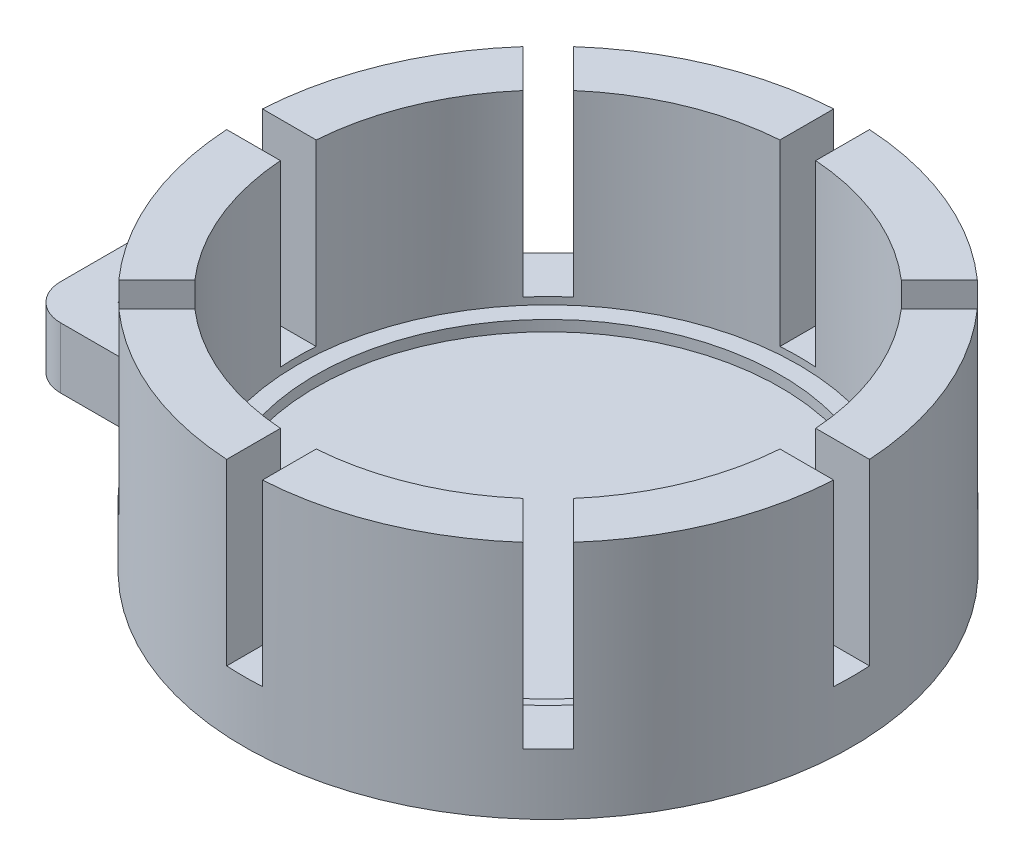
SolidWorks part; units mm, degrees
ref_plane "Спереди" through (0, 0, 0) normal (0, 0, 1) x (1, 0, 0)
ref_plane "Сверху" through (0, 0, 0) normal (0, 1, 0) x (1, 0, 0)
ref_plane "Справа" through (0, 0, 0) normal (1, 0, 0) x (0, 0, -1)
sketch "Эскиз1" plane through (0, 0, 0) normal (0, 1, 0) x (1, 0, 0)
  circle A0 centre (0, 0) radius 8.5
  dimension "D1" = 17
extrude "Бобышка-Вытянуть1" add sketch "Эскиз1" along normal blind 1.2
sketch "Эскиз2" plane through (0, 1.2, 0) normal (0, 1, 0) x (1, 0, 0)
  circle A0 centre (0, 0) radius 7
  circle A1 centre (0, 0) radius 8.5 construction
  circle A2 centre (0, 0) radius 8.5
  dimension "D1" = 14
extrude "Бобышка-Вытянуть2" add sketch "Эскиз2" along normal blind 5.5
sketch "Эскиз3" plane through (0, 1.2, 0) normal (0, 1, 0) x (1, 0, 0)
  circle A0 centre (0, 0) radius 7 construction
  circle A1 centre (0, 0) radius 7
  circle A2 centre (0, 0) radius 6.5
  dimension "D1" = 13
extrude "Бобышка-Вытянуть3" add sketch "Эскиз3" along normal blind 0.3
sketch "Эскиз4" plane through (0, 6.7, 0) normal (0, 1, 0) x (1, 0, 0)
  line L1 (0.5, 5.6513) -> (-0.5, 5.6513)
  line L2 (0.5, 5.6513) -> (0.5, 9.7336)
  line L3 (0.5, 9.7336) -> (-0.5, 9.7336)
  line L4 (-0.5, 5.6513) -> (-0.5, 9.7336)
  line L5 (0.5, 5.6513) -> (-0.5, 9.7336) construction
  line L6 (0.5, 9.7336) -> (-0.5, 5.6513) construction
  point P0 (0, 7.6924)
  point P5 (0, 0)
  dimension "D1" = 1
extrude "Вырез-Вытянуть1" cut sketch "Эскиз4" against normal blind 5
pattern_circular "Круговой массив1" count 8 over 360 about axis through (0, 0, 0) along (0, 1, 0) of "Вырез-Вытянуть1"
sketch "Эскиз5" plane through (0, 0, 0) normal (0, -1, 0) x (1, 0, 0)
  line L1 (-11.124, -2.5) -> (-8.124, -2.5)
  line L2 (-12.124, -1.5) -> (-12.124, 1.5)
  line L3 (-11.124, 2.5) -> (-8.124, 2.5)
  line L5 (-12.124, -2.5) -> (-8.124, 2.5) construction
  line L6 (-12.124, 2.5) -> (-8.124, -2.5) construction
  line L7 (-9.424, 1.2) -> (-10.824, 1.2)
  line L8 (-9.424, 1.2) -> (-9.424, -1.2)
  line L9 (-9.424, -1.2) -> (-10.824, -1.2)
  line L10 (-10.824, 1.2) -> (-10.824, -1.2)
  line L11 (-9.424, 1.2) -> (-10.824, -1.2) construction
  line L12 (-9.424, -1.2) -> (-10.824, 1.2) construction
  circle A0 centre (0, 0) radius 8.5 construction
  arc A1 (-8.124, 2.5) -> (-8.124, -2.5) centre (0, 0) ccw
  arc A2 (-11.124, 2.5) -> (-12.124, 1.5) centre (-11.124, 1.5) ccw
  arc A3 (-12.124, -1.5) -> (-11.124, -2.5) centre (-11.124, -1.5) ccw
  point P0 (-10.124, 0)
  point P7 (-10.124, 0)
  dimension "D5" = 1
  dimension "D1" = 5
  dimension "D2" = 4
  dimension "D3" = 1.3
  dimension "D4" = 1.3
extrude "Бобышка-Вытянуть4" add sketch "Эскиз5" against normal up to surface (1.7 mm away) up to face at (-7.7419, 1.7, 0)
